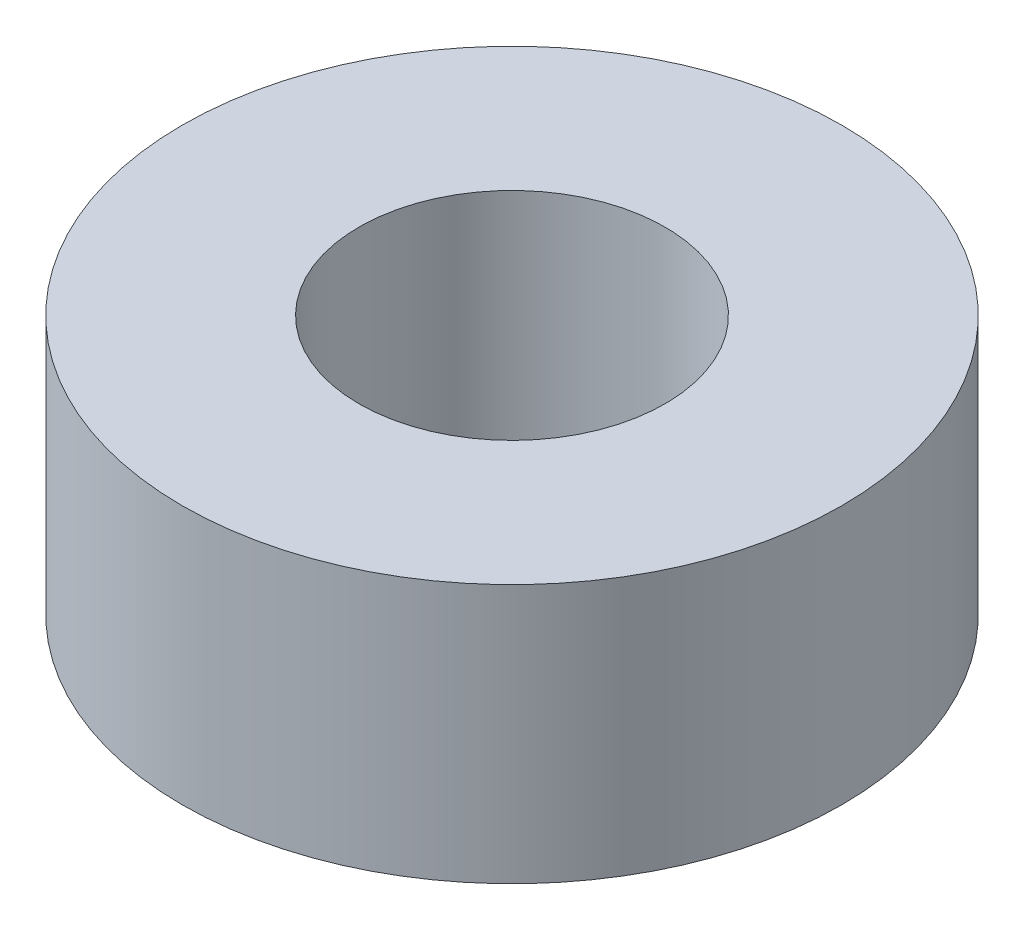
SolidWorks part; units mm, degrees
ref_plane "Front Plane" through (0, 0, 0) normal (0, 0, 1) x (1, 0, 0)
ref_plane "Top Plane" through (0, 0, 0) normal (0, 1, 0) x (1, 0, 0)
ref_plane "Right Plane" through (0, 0, 0) normal (1, 0, 0) x (0, 0, -1)
sketch "Sketch1" plane through (0, 0, 0) normal (0, 1, 0) x (1, 0, 0)
  circle A0 centre (0, 0) radius 1.625
  circle A1 centre (0, 0) radius 3.5
  dimension "D1" = 7
  dimension "D2" = 3.25
extrude "Boss-Extrude1" add sketch "Sketch1" along normal blind 2.75 contours A1 A0
